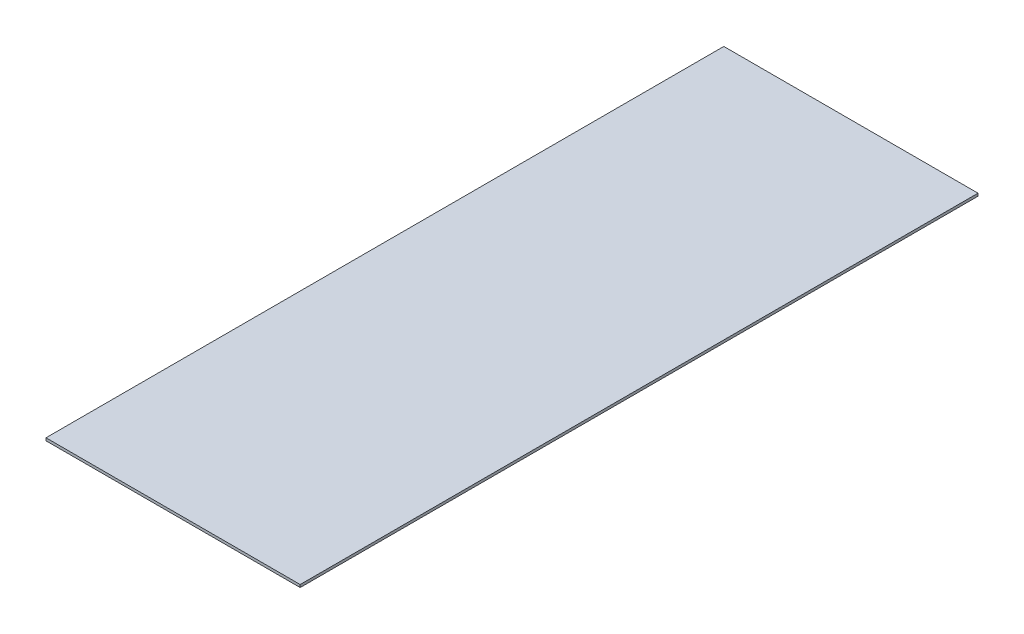
SolidWorks part; units mm, degrees
material "ASTM A36 Acero"
ref_plane "Alzado" through (0, 0, 0) normal (0, 0, 1) x (1, 0, 0)
ref_plane "Planta" through (0, 0, 0) normal (0, 1, 0) x (1, 0, 0)
ref_plane "Vista lateral" through (0, 0, 0) normal (1, 0, 0) x (0, 0, -1)
sketch "Croquis1" plane through (0, 0, 0) normal (0, 1, 0) x (1, 0, 0)
  line L1 (-457.2, -1219.2) -> (457.2, -1219.2)
  line L2 (-457.2, -1219.2) -> (-457.2, 1219.2)
  line L3 (-457.2, 1219.2) -> (457.2, 1219.2)
  line L4 (457.2, -1219.2) -> (457.2, 1219.2)
  line L5 (-457.2, -1219.2) -> (457.2, 1219.2) construction
  line L6 (-457.2, 1219.2) -> (457.2, -1219.2) construction
  point P0 (0, 0)
  dimension "D1" = 2438.4
  dimension "D2" = 914.4
extrude "Saliente-Extruir1" add sketch "Croquis1" along normal blind 9.5
